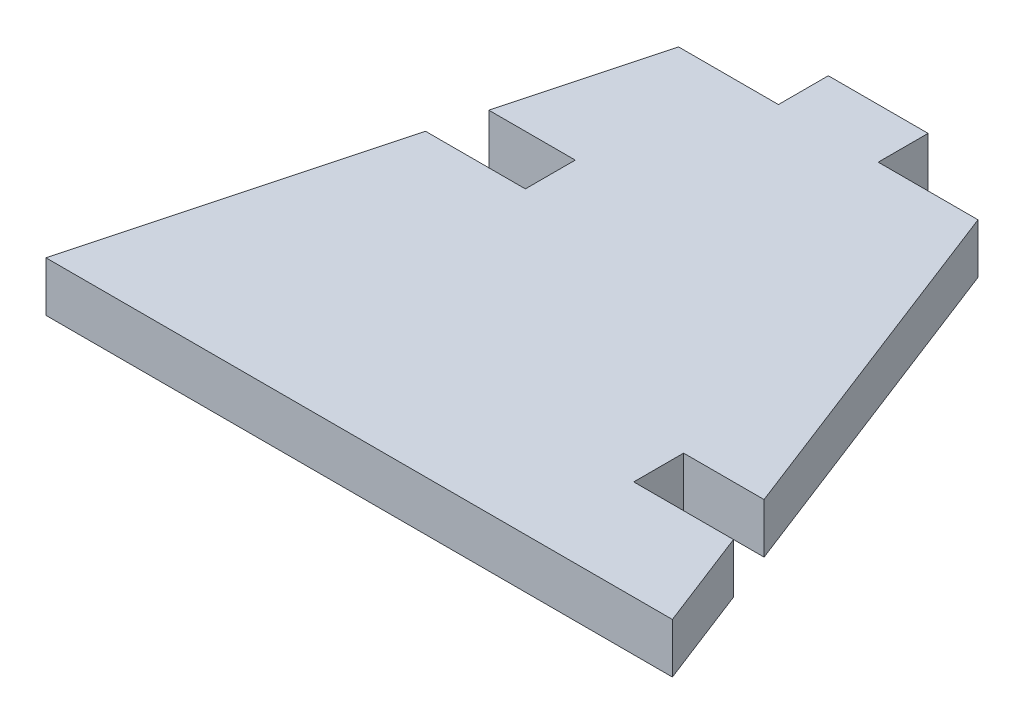
SolidWorks part; units mm, degrees
ref_plane "Front Plane" through (0, 0, 0) normal (0, 0, 1) x (1, 0, 0)
ref_plane "Top Plane" through (0, 0, 0) normal (0, 1, 0) x (1, 0, 0)
ref_plane "Right Plane" through (0, 0, 0) normal (1, 0, 0) x (0, 0, -1)
sketch "Sketch1" plane through (0, 0, 0) normal (0, 1, 0) x (1, 0, 0)
  line L0 (-153.661, 0) -> (145.3767, 0) construction
  line L1 (0, 100) -> (0, -77.6322) construction
  line L2 (0, 0) -> (87.5131, 0)
  line L3 (87.5131, 0) -> (79.7633, 20)
  line L4 (79.7633, 20) -> (59.7633, 20)
  line L5 (59.7633, 20) -> (59.7633, 30)
  line L6 (59.7633, 30) -> (75.8885, 30)
  line L7 (75.8885, 30) -> (48.7645, 100)
  line L10 (28.7645, 110) -> (8.7645, 110)
  line L11 (8.7645, 110) -> (8.7645, 100)
  line L12 (8.7645, 100) -> (-11.2355, 100)
  line L13 (-11.2355, 100) -> (-19.274, 70)
  line L14 (-19.274, 70) -> (-1.9535, 70)
  line L15 (-1.9535, 70) -> (-1.9535, 60)
  line L16 (-1.9535, 60) -> (-21.9535, 60)
  line L17 (-21.9535, 60) -> (-38.0305, 0)
  line L18 (-38.0305, 0) -> (0, 0)
  line L19 (28.7645, 110) -> (28.7645, 100)
  line L20 (28.7645, 100) -> (48.7645, 100)
  dimension "D1" = 75
  dimension "D2" = 60
  dimension "D3" = 20
  dimension "D4" = 10
  dimension "D5" = 20
  dimension "D6" = 20
  dimension "D7" = 10
  dimension "D8" = 60
  dimension "D9" = 10
  dimension "D10" = 20
  dimension "D11" = 20
  dimension "D12" = 100
extrude "Boss-Extrude1" add sketch "Sketch1" along normal blind 10
